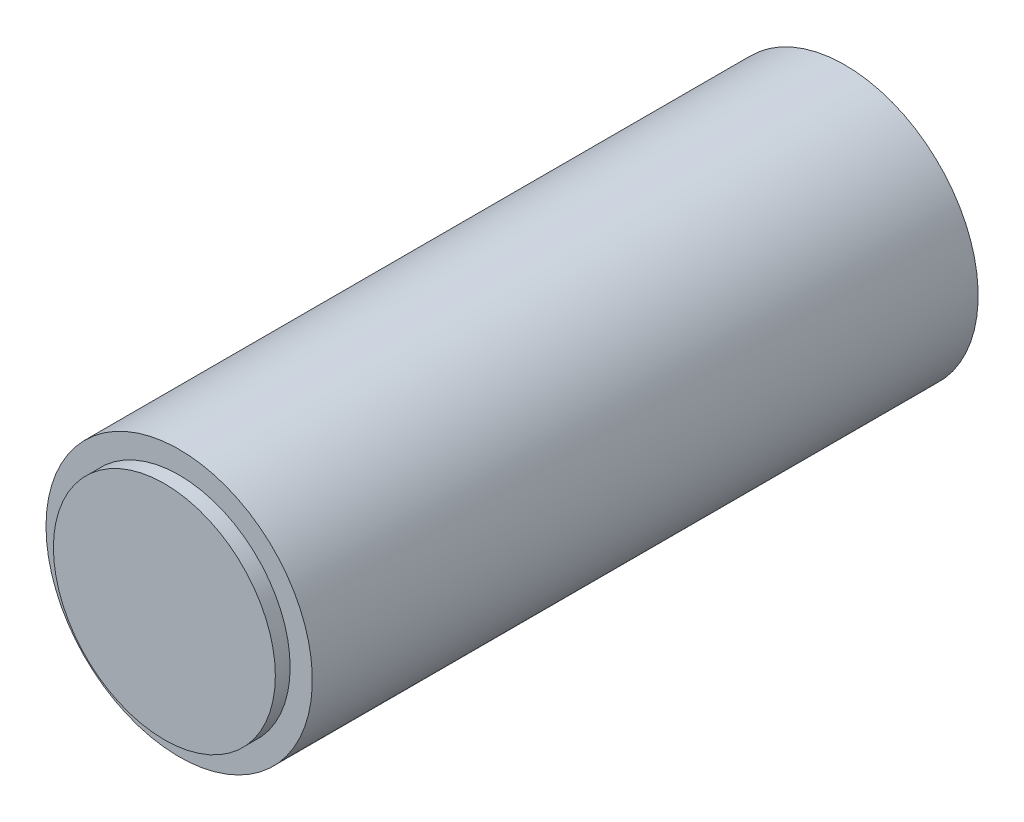
SolidWorks part; units mm, degrees
material "ABS"
ref_plane "Front Plane" through (0, 0, 0) normal (0, 0, 1) x (1, 0, 0)
ref_plane "Top Plane" through (0, 0, 0) normal (0, 1, 0) x (1, 0, 0)
ref_plane "Right Plane" through (0, 0, 0) normal (1, 0, 0) x (0, 0, -1)
sketch "Sketch1" plane through (0, 0, 0) normal (0, 0, 1) x (1, 0, 0)
  circle A0 centre (0, 0) radius 9
  dimension "D1" = 18
extrude "Boss-Extrude1" add sketch "Sketch1" along normal blind 45
sketch "Sketch2" plane through (0, 0, 45) normal (0, 0, 1) x (1, 0, 0)
  circle A0 centre (0, 0) radius 7.5
  dimension "D1" = 15
extrude "Boss-Extrude2" add sketch "Sketch2" along normal blind 1
